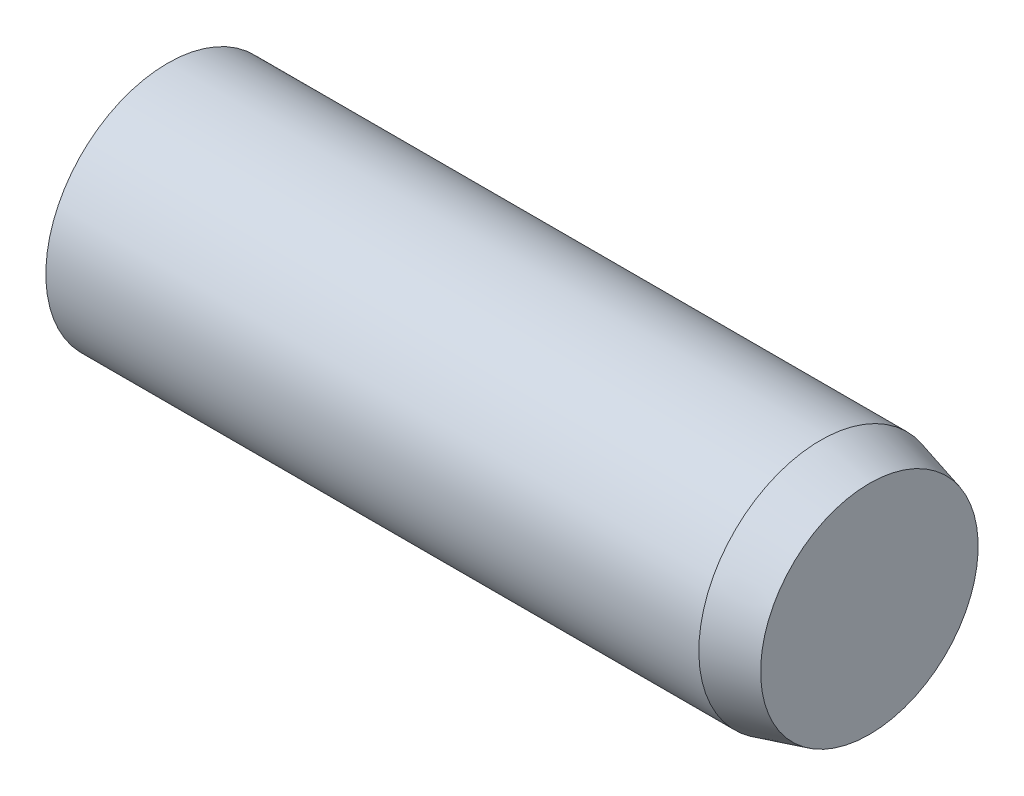
SolidWorks part; units mm, degrees
ref_plane "Plane1" through (0, 0, 0) normal (0, 0, 1) x (1, 0, 0)
ref_plane "Plane2" through (0, 0, 0) normal (0, 1, 0) x (1, 0, 0)
ref_plane "Plane3" through (0, 0, 0) normal (1, 0, 0) x (0, 0, -1)
sketch "BodySke" plane through (0, 0, 0) normal (0, 0, 1) x (1, 0, 0)
  line L0 (0, 0) -> (40.9091, 0) construction
  line L1 (28, 5) -> (30, 4.4641)
  line L2 (1.2, 5) -> (28, 5)
  line L3 (30, 4.4641) -> (30, 0)
  line L4 (0, 0) -> (30, 0)
  arc A0 (1.2, 5) -> (0, 0) centre (11.0167, 0) ccw
  dimension "D1" = 15
  dimension "Diameter" = 10
  dimension "Length" = 30
  dimension "Crown_ht" = 1.2
  dimension "Chamfer_len" = 2
revolve "Body" add sketch "BodySke" angle 360 about L0
equation "' \"D1@BodySke\" = \"Length@BodySke\""
